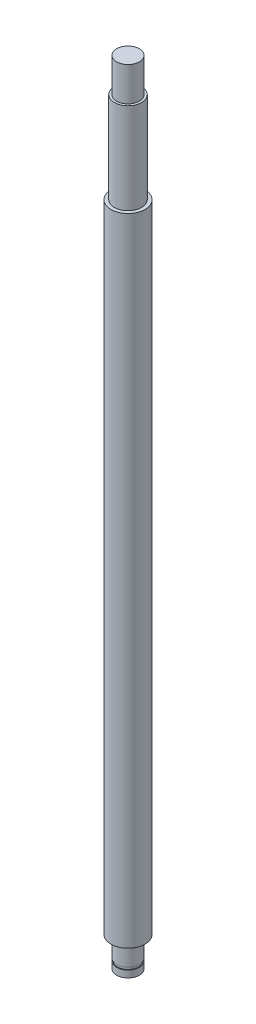
SolidWorks part; units mm, degrees
material "SKD11淬火HRC56-60"
ref_plane "前基準面" through (0, 0, 0) normal (0, 0, 1) x (1, 0, 0)
ref_plane "上基準面" through (0, 0, 0) normal (0, 1, 0) x (1, 0, 0)
ref_plane "右基準面" through (0, 0, 0) normal (1, 0, 0) x (0, 0, -1)
sketch "草图1" plane through (0, 0, 0) normal (0, 1, 0) x (1, 0, 0)
  circle A0 centre (0, 0) radius 7.5
  dimension "D1" = 15
extrude "凸台-拉伸1" add sketch "草图1" along normal blind 280
sketch "草图2" plane through (0, 280, 0) normal (0, 1, 0) x (1, 0, 0)
  circle A0 centre (0, 0) radius 6
  dimension "D1" = 12
extrude "凸台-拉伸2" add sketch "草图2" along normal blind 40
cosmetic thread "装饰螺纹线1" parameters "D1"=10, "D2"=10
sketch "草图3" plane through (0, 320, 0) normal (0, 1, 0) x (1, 0, 0)
  circle A0 centre (0, 0) radius 5
  dimension "D1" = 10
extrude "凸台-拉伸3" add sketch "草图3" along normal blind 15
sketch "草图4" plane through (0, 0, 0) normal (0, -1, 0) x (1, 0, 0)
  circle A0 centre (0, 0) radius 5
  dimension "D1" = 10
extrude "凸台-拉伸4" add sketch "草图4" along normal blind 9
sketch "草图5" plane through (0, -9, 0) normal (0, -1, 0) x (1, 0, 0)
  circle A0 centre (0, 0) radius 4.65
  dimension "D1" = 9.3
extrude "凸台-拉伸5" add sketch "草图5" along normal blind 1.1
sketch "草图6" plane through (0, -10.1, 0) normal (0, -1, 0) x (1, 0, 0)
  circle A0 centre (0, 0) radius 5
  dimension "D1" = 10
extrude "凸台-拉伸6" add sketch "草图6" along normal blind 3
